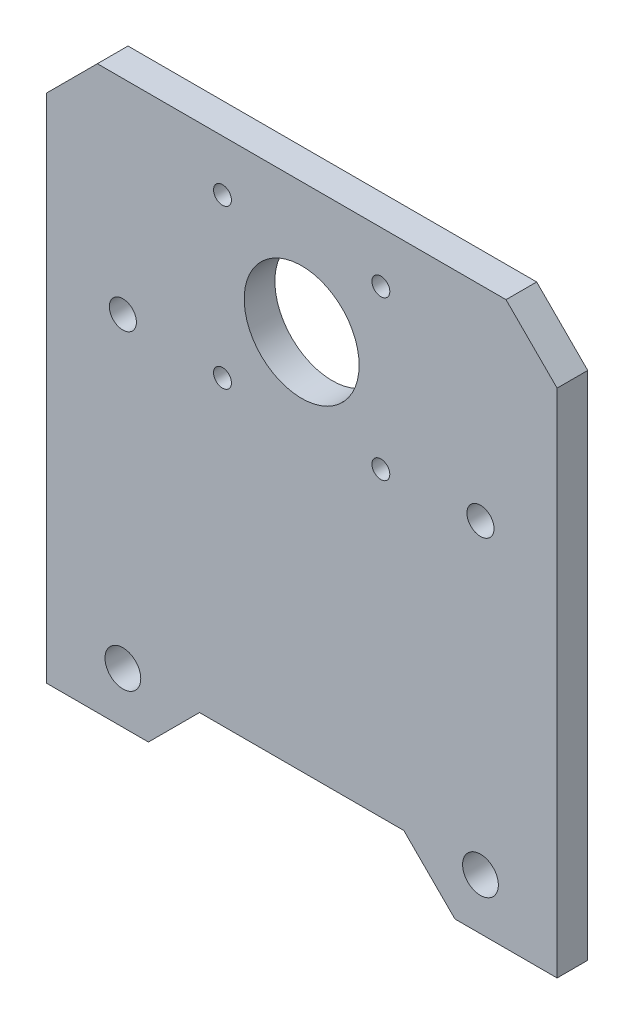
SolidWorks part; units mm, degrees
material "ABS"
ref_plane "Alzado" through (0, 0, 0) normal (0, 0, 1) x (1, 0, 0)
ref_plane "Planta" through (0, 0, 0) normal (0, 1, 0) x (1, 0, 0)
ref_plane "Vista lateral" through (0, 0, 0) normal (1, 0, 0) x (0, 0, -1)
sketch "Croquis1" plane through (0, 0, 0) normal (0, 0, 1) x (1, 0, 0)
  line L5 (100, 100) -> (100, 0)
  line L6 (100, 0) -> (80, 0)
  line L7 (80, 0) -> (70, 10)
  line L8 (70, 10) -> (30, 10)
  line L9 (30, 10) -> (20, 0)
  line L10 (20, 0) -> (0, 0)
  line L11 (0, 0) -> (0, 100)
  line L17 (0, 100) -> (10, 110)
  line L18 (10, 110) -> (90, 110)
  line L19 (90, 110) -> (100, 100)
  line L20 (65.5, 100) -> (57.955, 92.455) construction
  line L21 (34.5, 100) -> (50, 84.5) construction
  line L22 (57.955, 76.545) -> (65.5, 69) construction
  line L23 (50, 84.5) -> (34.5, 69) construction
  circle A6 centre (15, 70) radius 2.65
  circle A9 centre (15, 10) radius 3.5
  circle A10 centre (85, 10) radius 3.5
  circle A11 centre (34.5, 100) radius 1.75
  circle A12 centre (65.5, 100) radius 1.75
  circle A13 centre (65.5, 69) radius 1.75
  circle A14 centre (34.5, 69) radius 1.75
  circle A15 centre (50, 84.5) radius 11.25
  circle A16 centre (85, 70) radius 2.65
  dimension "D2" = 22.5
  dimension "D3" = 15.5
  dimension "D9" = 5.3
  dimension "D12" = 7
  dimension "D6" = 3.5
  dimension "D4" = 15.5
  dimension "D5" = 70
  dimension "D7" = 31
  dimension "D13" = 15
  dimension "D14" = 10
  dimension "D15" = 15
  dimension "D16" = 10
extrude "Saliente-Extruir1" add sketch "Croquis1" along normal blind 6
